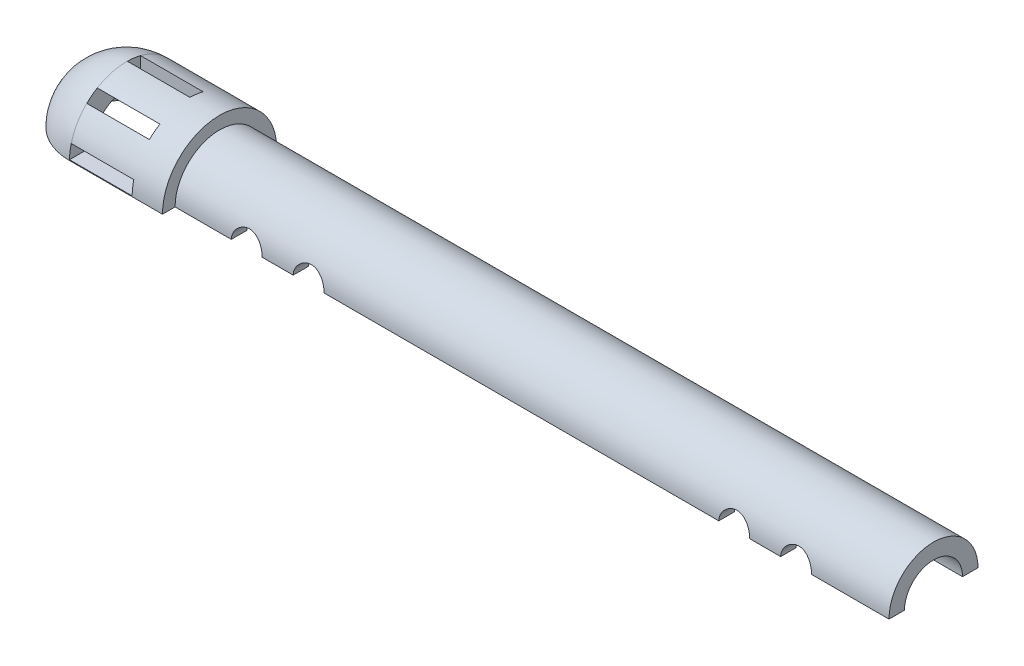
SolidWorks part; units mm, degrees
ref_plane "Front Plane" through (0, 0, 0) normal (0, 0, 1) x (1, 0, 0)
ref_plane "Top Plane" through (0, 0, 0) normal (0, 1, 0) x (1, 0, 0)
ref_plane "Right Plane" through (0, 0, 0) normal (1, 0, 0) x (0, 0, -1)
sketch "Sketch1" plane through (0, 0, 0) normal (0, 1, 0) x (1, 0, 0)
  line L1 (-7.9091, 1.25) -> (72.379, 1.25)
  line L5 (74.914, 3.25) -> (-13.6552, 3.25)
  line L9 (-16.6552, 4.88) -> (-25.6663, 4.88)
  line L10 (-7.9091, 1.25) -> (-10.9052, 1.25)
  line L11 (-16.6552, 1.25) -> (-16.6552, 1.8792)
  line L12 (-16.6552, 1.8792) -> (-25.6663, 1.8792)
  line L14 (-33.0463, -2.5) -> (-30.0455, -2.5)
  line L17 (74.914, 3.25) -> (78.609, 3.25)
  line L18 (78.609, 3.25) -> (78.609, 1.25)
  line L19 (-16.6552, 4.88) -> (-13.6552, 4.88)
  line L20 (-13.6552, 4.88) -> (-13.6552, 3.25)
  line L21 (72.379, 1.25) -> (72.379, 0)
  line L22 (72.379, 0) -> (74.609, 0)
  line L23 (74.609, 0) -> (74.609, 1.25)
  line L24 (74.609, 1.25) -> (78.609, 1.25)
  line L25 (-12.6352, 1.25) -> (-12.6352, 0)
  line L26 (-12.6352, 0) -> (-10.9052, 0)
  line L27 (-10.9052, 0) -> (-10.9052, 1.25)
  line L28 (-12.6352, 1.25) -> (-16.6552, 1.25)
  arc A1 (-25.6663, 4.88) -> (-33.0463, -2.5) centre (-25.6663, -2.5) ccw
  arc A2 (-25.6663, 1.8792) -> (-30.0455, -2.5) centre (-25.6663, -2.5) ccw
  dimension "D1" = 3.75
  dimension "D2" = 2
  dimension "D3" = 2.23
  dimension "D4" = 4
  dimension "D5" = 2.5
  dimension "D6" = 4.02
  dimension "D7" = 2.5
  dimension "D8" = 1.73
revolve "Revolve6" add sketch "Sketch1" angle 180 about L14
sketch "Sketch2" plane through (0, 0, 0) normal (0, 1, 0) x (1, 0, 0)
  line L0 (-25.6663, -0.7005) -> (-17.5748, -0.7005)
  line L1 (-25.6663, -9.88) -> (-25.6663, 4.88) construction
  line L2 (-17.5748, -0.7005) -> (-17.5748, -2.4039)
  line L3 (-17.5748, -2.4039) -> (-25.6663, -2.4039)
  line L4 (-25.6663, -2.4039) -> (-25.6663, -0.7005)
extrude "Cut-Extrude1" cut sketch "Sketch2" along normal blind 10
pattern_circular "CirPattern1" count 8 every 45 about axis through (0, 0, 2.5) along (1, 0, 0) of "Cut-Extrude1"
sketch "Sketch3" plane through (0, 0, 0) normal (0, 0, 1) x (1, 0, 0)
  line L0 (78.609, 0) -> (-13.6552, 0) construction
  line L1 (78.609, 0) -> (78.609, 3.75) construction
  line L2 (78.609, 0) -> (78.609, 5.75) construction
  circle A0 centre (66.609, 0) radius 2
  circle A1 centre (58.609, 0) radius 2
  circle A2 centre (3.609, 0) radius 2
  circle A3 centre (-4.391, 0) radius 2
  point P14 (78.609, 2.875)
  dimension "D1" = 4
  dimension "D2" = 12
  dimension "D3" = 20
  dimension "D4" = 8
  dimension "D5" = 75
extrude "Cut-Extrude4" cut sketch "Sketch3" against normal through all both and the other way through all
